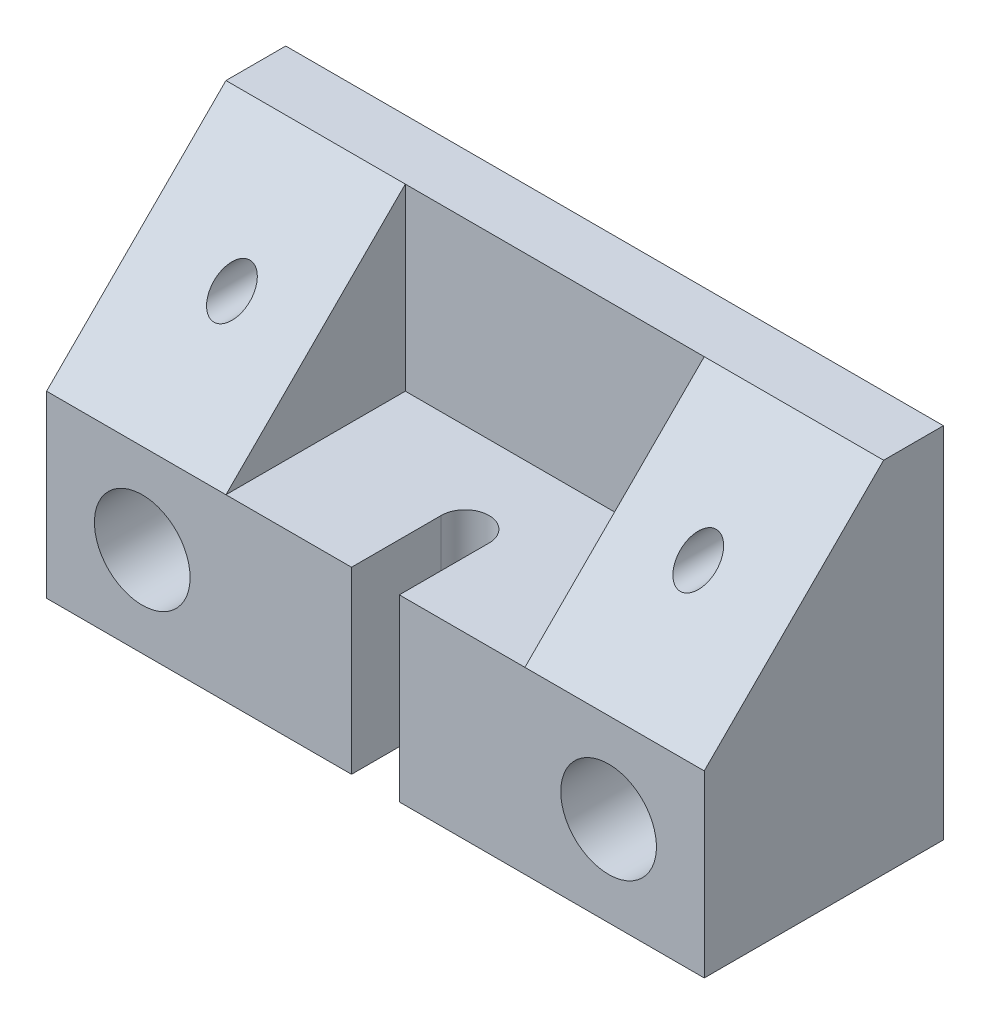
SolidWorks part; units mm, degrees
ref_plane "前视基准面" through (0, 0, 0) normal (0, 0, 1) x (1, 0, 0)
ref_plane "上视基准面" through (0, 0, 0) normal (0, 1, 0) x (1, 0, 0)
ref_plane "右视基准面" through (0, 0, 0) normal (1, 0, 0) x (0, 0, -1)
sketch "草图1" plane through (0, 0, 0) normal (0, 0, 1) x (1, 0, 0)
  line L1 (0, 0) -> (0.55, 0)
  line L2 (0, 0) -> (0, 0.3)
  line L3 (0, 0.3) -> (0.55, 0.3)
  line L4 (0.55, 0) -> (0.55, 0.3)
  dimension "D1" = 0.55
  dimension "D2" = 0.3
extrude "凸台-拉伸1" add sketch "草图1" along normal blind 0.2
sketch "草图2" plane through (0, 0, 0) normal (-1, 0, 0) x (0, 0, 1)
  line L0 (0.2, 0.3) -> (0.2, 0.15)
  line L1 (0.2, 0.3) -> (0.2, 0) construction
  line L2 (0.2, 0.15) -> (0.05, 0.3)
  line L3 (0.2, 0.3) -> (0, 0.3) construction
  line L4 (0.05, 0.3) -> (0.2, 0.3)
  dimension "D1" = 45
  dimension "D2" = 0.15
extrude "切除-拉伸1" cut sketch "草图2" against normal up to next
sketch "草图3" plane through (0, 0.3, 0) normal (0, 1, 0) x (1, 0, 0)
  line L0 (0.275, 0) -> (0.275, -0.2) construction
  line L1 (0.55, 0) -> (0, 0) construction
  line L2 (0.55, -0.2) -> (0, -0.2) construction
  line L3 (0.55, -0.05) -> (0, -0.05) construction
  line L4 (0.15, -0.2) -> (0.4, -0.2)
  line L5 (0.15, -0.2) -> (0.15, -0.05)
  line L6 (0.15, -0.05) -> (0.4, -0.05)
  line L7 (0.4, -0.2) -> (0.4, -0.05)
  line L8 (0.15, -0.2) -> (0.4, -0.05) construction
  line L9 (0.15, -0.05) -> (0.4, -0.2) construction
  point P6 (0.275, -0.125)
  dimension "D1" = 0.25
extrude "切除-拉伸2" cut sketch "草图3" against normal blind 0.15
sketch "草图4" plane through (0, 0.15, 0) normal (0, 1, 0) x (1, 0, 0)
  line L0 (0.275, 0) -> (0.275, -0.2) construction
  line L1 (0.15, -0.2) -> (0.4, -0.2) construction
  line L2 (0.275, -0.275) -> (0.275, -0.125) construction
  line L3 (0.255, -0.275) -> (0.255, -0.125)
  line L4 (0.295, -0.275) -> (0.295, -0.125)
  line L5 (0.55, 0) -> (0, 0) construction
  arc A0 (0.255, -0.275) -> (0.295, -0.275) centre (0.275, -0.275) ccw
  arc A1 (0.295, -0.125) -> (0.255, -0.125) centre (0.275, -0.125) ccw
  point P6 (0.275, -0.2)
  dimension "D1" = 0.02
  dimension "D2" = 0.15
extrude "切除-拉伸3" cut sketch "草图4" against normal through all
sketch "草图5" plane through (0, 0, 0.2) normal (0, 0, 1) x (1, 0, 0)
  line L0 (0.275, 0.3) -> (0.275, 0) construction
  line L1 (0.4, 0.3) -> (0.15, 0.3) construction
  line L2 (0.255, 0) -> (0.295, 0) construction
  line L3 (0, 0.075) -> (0.55, 0.075) construction
  line L4 (0, 0.15) -> (0, 0) construction
  line L5 (0.55, 0) -> (0.55, 0.15) construction
  line L6 (0, 0.225) -> (0.55, 0.225) construction
  line L7 (0, 0.3) -> (0, 0.15) construction
  line L8 (0.55, 0.3) -> (0.55, 0.15) construction
  line L9 (0.08, 0.225) -> (0.08, 0.075) construction
  circle A0 centre (0.08, 0.075) radius 0.04
  circle A1 centre (0.08, 0.225) radius 0.015
  circle A2 centre (0.47, 0.075) radius 0.04
  circle A3 centre (0.47, 0.225) radius 0.015
  dimension "D1" = 0.03
  dimension "D2" = 0.08
  dimension "D3" = 0.08
extrude "切除-拉伸4" cut sketch "草图5" against normal through all
